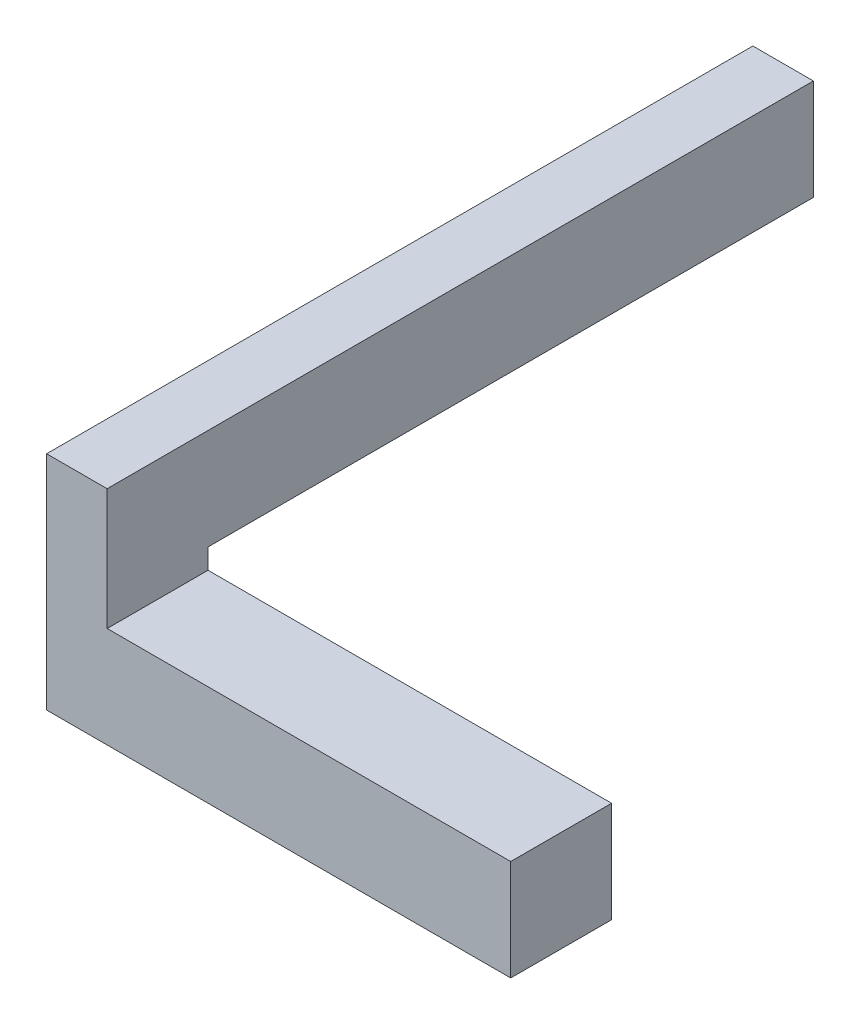
SolidWorks part; units mm, degrees
ref_plane "Front Plane" through (0, 0, 0) normal (0, 0, 1) x (1, 0, 0)
ref_plane "Top Plane" through (0, 0, 0) normal (0, 1, 0) x (1, 0, 0)
ref_plane "Right Plane" through (0, 0, 0) normal (1, 0, 0) x (0, 0, -1)
sketch "Sketch1" plane through (0, 0, 0) normal (0, 0, 1) x (1, 0, 0)
  line L1 (-3, -5) -> (3, -5)
  line L2 (-3, -5) -> (-3, 5)
  line L3 (-3, 5) -> (3, 5)
  line L4 (3, -5) -> (3, 5)
  line L5 (-3, -5) -> (3, 5) construction
  line L6 (-3, 5) -> (3, -5) construction
  point P0 (0, 0)
  dimension "D1" = 6
  dimension "D2" = 10
extrude "Boss-Extrude1" add sketch "Sketch1" along normal blind 70
sketch "Sketch2" plane through (0, -5, 0) normal (0, -1, 0) x (1, 0, 0)
  line L0 (-3, 70) -> (-3, 0) construction
  line L1 (3, 70) -> (-3, 70)
  line L2 (3, 70) -> (3, 60)
  line L3 (3, 60) -> (-3, 60)
  line L4 (-3, 70) -> (-3, 60)
  dimension "D1" = 10
extrude "Boss-Extrude2" add sketch "Sketch2" along normal blind 12
sketch "Sketch3" plane through (3, 0, 0) normal (1, 0, 0) x (0, 0, -1)
  line L0 (-60, -17) -> (-60, -5) construction
  line L1 (-70, -17) -> (-60, -17)
  line L2 (-70, -17) -> (-70, -7)
  line L3 (-70, -7) -> (-60, -7)
  line L4 (-60, -17) -> (-60, -7)
  dimension "D1" = 10
extrude "Boss-Extrude3" add sketch "Sketch3" along normal blind 40
